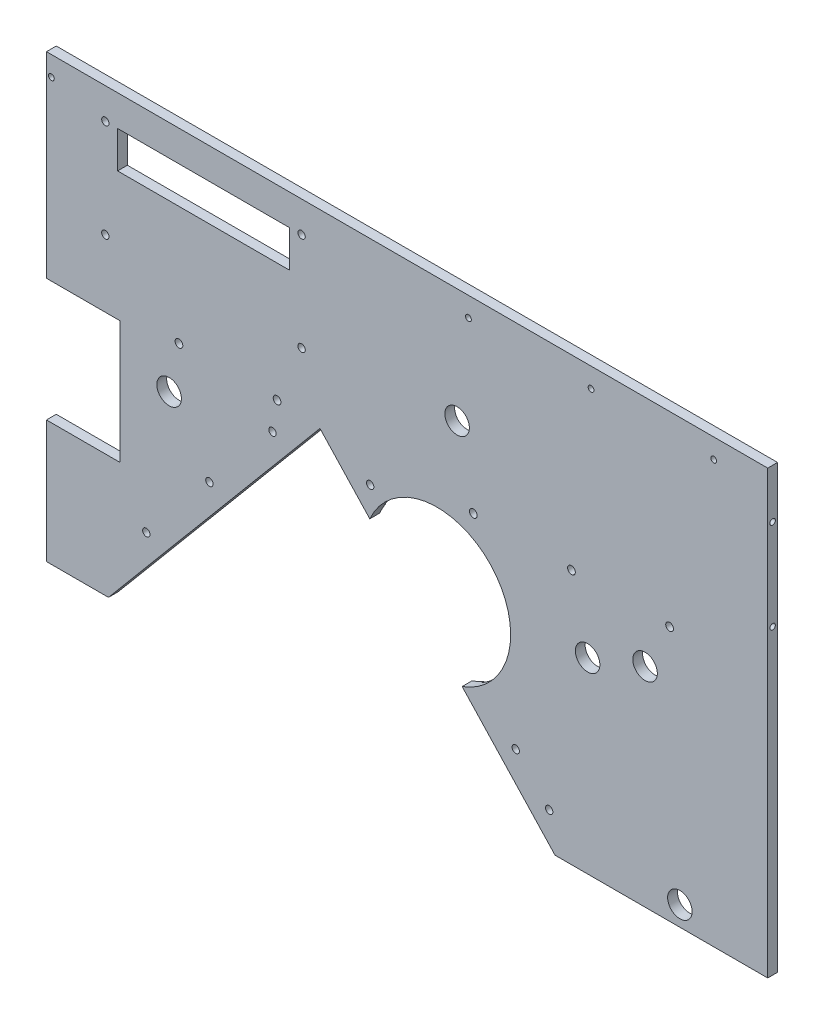
SolidWorks part; units mm, degrees
ref_plane "Front Plane" through (0, 0, 0) normal (0, 0, 1) x (1, 0, 0)
ref_plane "Top Plane" through (0, 0, 0) normal (0, 1, 0) x (1, 0, 0)
ref_plane "Right Plane" through (0, 0, 0) normal (1, 0, 0) x (0, 0, -1)
sketch "Sketch1" plane through (0, 0, 0) normal (0, 0, 1) x (1, 0, 0)
  line L0 (373.38, 127) -> (0, 127) construction
  line L1 (0, 0) -> (373.38, 0)
  line L2 (0, 0) -> (0, 228.6)
  line L3 (0, 228.6) -> (373.38, 228.6)
  line L4 (373.38, 0) -> (373.38, 228.6)
  line L5 (13.716, 228.6) -> (13.716, 0) construction
  line L6 (13.716, 0) -> (141.5948, 152.4)
  line L7 (141.5948, 152.4) -> (141.5948, 0)
  line L8 (141.5948, 0) -> (13.716, 0)
  line L9 (24.3726, 0) -> (141.5948, 139.7)
  line L10 (141.5948, 152.4) -> (141.5948, -50.8)
  line L11 (141.5948, -50.8) -> (331.0818, -50.8)
  line L12 (331.0818, -50.8) -> (141.5948, 152.4)
  line L13 (141.5948, 139.7) -> (319.2389, -50.8)
  dimension "D1" = 373.38
  dimension "D2" = 228.6
  dimension "D3" = 127
  dimension "D4" = 13.716
  dimension "D5" = 152.4
  dimension "D6" = 12.7
  dimension "D7" = 50
  dimension "D8" = 203.2
  dimension "D9" = 47
ref_plane "Plane1" through (0, 0, 0) normal (0, 0, 1) x (1, 0, 0)
sketch "Sketch2" plane through (0, 0, 0) normal (0, 0, 1) x (1, 0, 0)
  line L0 (32.1017, 0) -> (141.5948, 130.4888)
  line L1 (0, 228.6) -> (373.38, 228.6)
  line L2 (0, 228.6) -> (0, 0)
  line L3 (0, 0) -> (373.38, 0)
  line L4 (373.38, 228.6) -> (373.38, 0)
  line L5 (141.5948, 152.4) -> (141.5948, 0) construction
  line L6 (141.5948, 130.4888) -> (263.2776, 0)
  line L7 (263.2776, 0) -> (32.1017, 0)
  dimension "D1" = 50
  dimension "D2" = 47
extrude "Boss-Extrude1" add sketch "Sketch2" along normal blind 5.08 contours L0 L6 L3 L4 L1 L2
sketch "Sketch3" plane through (0, 0, 5.08) normal (0, 0, 1) x (1, 0, 0)
  line L0 (13.716, 0) -> (24.3726, 0)
  line L1 (24.3726, 0) -> (141.5948, 139.7)
  line L2 (141.5948, 139.7) -> (271.8671, 0)
  line L3 (0, 0) -> (373.38, 0) construction
  line L4 (141.5948, 139.7) -> (319.2389, -50.8) construction
  line L5 (271.8671, 0) -> (283.7101, 0)
  line L6 (331.0818, -50.8) -> (141.5948, 152.4) construction
  line L7 (283.7101, 0) -> (141.5948, 152.4)
  line L8 (141.5948, 152.4) -> (13.716, 0)
ref_plane "Plane2" through (0, 0, 0) normal (0, 0, -1) x (-1, 0, 0)
sketch "Sketch4" plane through (0, 0, 0) normal (0, 0, -1) x (-1, 0, 0)
  line L0 (-283.7101, 0) -> (-271.8671, 0)
  line L1 (-271.8671, 0) -> (-141.5948, 139.7)
  line L2 (-141.5948, 139.7) -> (-24.3726, 0)
  line L3 (-24.3726, 0) -> (-13.716, 0)
  line L4 (-13.716, 0) -> (-141.5948, 152.4)
  line L5 (-141.5948, 152.4) -> (-283.7101, 0)
extrude "Cut-Extrude2" cut sketch "Sketch4" against normal blind 1.27
sketch "Sketch5" plane through (0, 0, 5.08) normal (0, 0, 1) x (1, 0, 0)
  line L0 (0, 0) -> (0, 228.6) construction
  line L1 (0, 127) -> (38.1, 127)
  line L2 (0, 127) -> (0, 63.5)
  line L3 (0, 63.5) -> (38.1, 63.5)
  line L4 (38.1, 127) -> (38.1, 63.5)
  line L5 (0, 0) -> (373.38, 0) construction
  dimension "D1" = 63.5
  dimension "D2" = 38.1
  dimension "D3" = 63.5
extrude "Cut-Extrude3" cut sketch "Sketch5" against normal blind 7.62
sketch "Sketch6" plane through (0, 0, 1.27) normal (0, 0, -1) x (-1, 0, 0)
  line L0 (-331.0818, -50.8) -> (-319.2389, -50.8) construction
  line L1 (-283.7101, 0) -> (-271.8671, 0) construction
  line L2 (-271.8671, 0) -> (-277.7886, 0) construction
  line L3 (-277.7886, 0) -> (-141.5948, 146.05) construction
  line L4 (-141.5948, 152.4) -> (-141.5948, 0) construction
  line L5 (-141.5948, 146.05) -> (-277.7886, 0) construction
  line L6 (0, 0) -> (-373.38, 0) construction
  line L7 (-331.0818, -50.8) -> (-141.5948, 152.4) construction
  line L8 (-24.3726, 0) -> (-13.716, 0) construction
  line L9 (-13.716, 0) -> (-19.0443, 0) construction
  line L10 (-19.0443, 0) -> (-141.5948, 146.05) construction
  circle A0 centre (-51.6979, 38.9151) radius 1.905
  circle A1 centre (-84.3515, 77.8301) radius 1.905
  circle A2 centre (-117.0051, 116.7452) radius 1.905
  circle A3 centre (-167.5789, 118.1854) radius 1.905
  circle A4 centre (-242.9329, 37.3782) radius 1.905
  circle A5 centre (-260.2557, 18.8018) radius 1.905
  dimension "D1" = 50.8
  dimension "D4" = 38.1
  dimension "D2" = 50.8
  dimension "D3" = 50.8
  dimension "D5" = 110.49
  dimension "D6" = 25.4
extrude "Cut-Extrude4" cut sketch "Sketch6" against normal blind 7.62
sketch "Sketch7" plane through (0, 0, 0) normal (0, 0, -1) x (-1, 0, 0)
  line L0 (-141.5948, 152.4) -> (-190.1142, 100.3692) construction
  line L1 (-331.0818, -50.8) -> (-141.5948, 152.4) construction
  line L2 (-190.1142, 100.3692) -> (-214.2986, 74.4347) construction
  circle A0 centre (-202.2064, 87.402) radius 38.1
extrude "Cut-Extrude5" cut sketch "Sketch7" against normal blind 7.62
sketch "Sketch8" plane through (0, 0, 0) normal (0, 0, -1) x (-1, 0, 0)
  line L0 (0, 228.6) -> (-373.38, 228.6) construction
  line L1 (0, 0) -> (0, 228.6) construction
  line L3 (-125.73, 212.598) -> (-36.83, 212.598)
  line L4 (-125.73, 212.598) -> (-125.73, 193.548)
  line L5 (-125.73, 193.548) -> (-36.83, 193.548)
  line L6 (-36.83, 212.598) -> (-36.83, 193.548)
  circle A0 centre (-132.08, 212.598) radius 1.905
  circle A1 centre (-30.48, 212.598) radius 1.905
  circle A2 centre (-132.08, 161.798) radius 1.905
  circle A3 centre (-30.48, 161.798) radius 1.905
  dimension "D1" = 50.8
  dimension "D2" = 50.8
  dimension "D3" = 16.002
  dimension "D4" = 16.002
  dimension "D5" = 101.6
  dimension "D6" = 101.6
  dimension "D7" = 30.48
  dimension "D8" = 88.9
  dimension "D9" = 6.35
  dimension "D10" = 19.05
  dimension "D11" = 16.002
extrude "Cut-Extrude6" cut sketch "Sketch8" against normal blind 7.62
sketch "Sketch9" plane through (0, 0, 0) normal (0, 0, -1) x (-1, 0, 0)
  line L0 (-371.8585, -1.4188) -> (-184.8692, 199.1026) construction
  line L1 (-331.0818, -50.8) -> (-141.5948, 152.4) construction
  line L3 (-228.1906, 59.5374) -> (-283.7101, 0) construction
  line L4 (-283.7101, 0) -> (-373.38, 0) construction
  line L5 (-373.38, 228.6) -> (-373.38, 0) construction
  circle A1 centre (-327.914, 10.16) radius 6.35
  circle A2 centre (-280.1391, 96.9381) radius 6.35
  circle A3 centre (-212.5804, 169.386) radius 6.35
  dimension "D1" = 99.06
  dimension "D2" = 63.5
  dimension "D3" = 10.16
  dimension "D4" = 45.466
  dimension "D5" = 99.06
extrude "Cut-Extrude7" cut sketch "Sketch9" against normal blind 7.62
sketch "Sketch10" plane through (0, 0, 0) normal (0, 0, -1) x (-1, 0, 0)
  line L0 (-373.38, 0) -> (-373.38, 228.6) construction
  line L1 (-283.7101, 0) -> (-373.38, 0) construction
  line L2 (0, 228.6) -> (0, 127) construction
  line L3 (0, 0) -> (-13.716, 0) construction
  circle A0 centre (-309.88, 107.95) radius 6.35
  circle A1 centre (-63.5, 107.95) radius 6.35
  dimension "D1" = 63.5
  dimension "D3" = 63.5
  dimension "D2" = 107.95
  dimension "D4" = 107.95
extrude "Cut-Extrude8" cut sketch "Sketch10" against normal blind 7.62
sketch "Sketch11" plane through (0, 0, 0) normal (0, 0, -1) x (-1, 0, 0)
  line L0 (-373.38, 218.44) -> (0, 218.44) construction
  line L1 (-373.38, 228.6) -> (-373.38, 0) construction
  line L2 (0, 228.6) -> (0, 127) construction
  line L3 (0, 228.6) -> (-373.38, 228.6) construction
  circle A0 centre (-345.44, 218.44) radius 1.5
  circle A1 centre (-281.94, 218.44) radius 1.5
  circle A2 centre (-218.44, 218.44) radius 1.5
  circle A3 centre (-2.54, 218.44) radius 1.5
  dimension "D2" = 63.5
  dimension "D1" = 10.16
  dimension "D3" = 63.5
  dimension "D4" = 215.9
  dimension "D5" = 2.54
extrude "Cut-Extrude9" cut sketch "Sketch11" against normal blind 25.4
sketch "Sketch12" plane through (0, 0, 5.08) normal (0, 0, 1) x (1, 0, 0)
  line L0 (373.38, 132.08) -> (0, 132.08) construction
  line L1 (373.38, 228.6) -> (373.38, 0) construction
  line L2 (0, 0) -> (32.1017, 0) construction
  circle A0 centre (322.58, 132.08) radius 2
  circle A1 centre (271.78, 132.08) radius 2
  circle A2 centre (220.98, 132.08) radius 2
  circle A3 centre (119.38, 132.08) radius 2
  circle A4 centre (68.58, 132.08) radius 2
  dimension "D2" = 50.8
  dimension "D6" = 50.8
  dimension "D1" = 132.08
  dimension "D3" = 50.8
  dimension "D4" = 50.8
  dimension "D5" = 101.6
extrude "Cut-Extrude10" cut sketch "Sketch12" against normal blind 381
sketch "Sketch13" plane through (373.38, 0, 0) normal (1, 0, 0) x (0, 0, -1)
  line L0 (-2.54, 228.6) -> (-2.54, 0) construction
  line L1 (-5.08, 228.6) -> (0, 228.6) construction
  line L2 (-5.08, 0) -> (0, 0) construction
  circle A0 centre (-2.54, 203.2) radius 1.4224
  circle A1 centre (-2.54, 156.21) radius 1.4224
  dimension "D1" = 25.4
  dimension "D2" = 46.99
extrude "Cut-Extrude11" cut sketch "Sketch13" against normal blind 12.7
